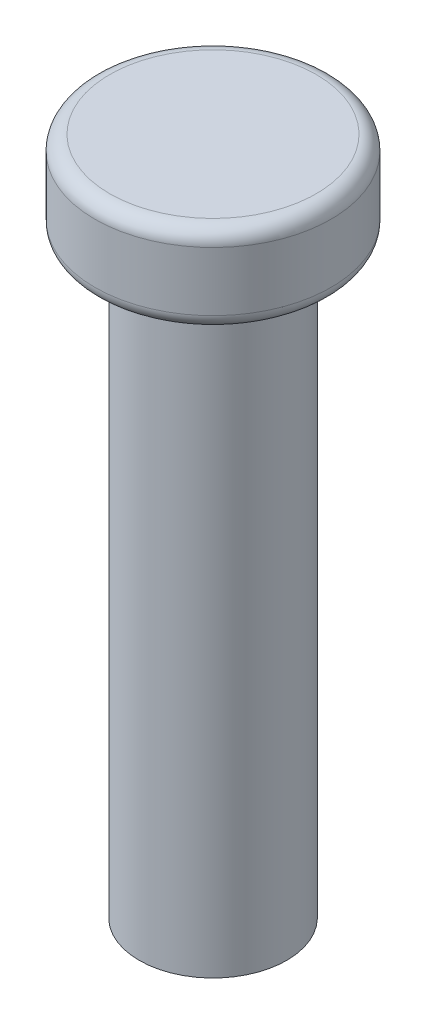
SolidWorks part; units mm, degrees
ref_plane "Front Plane" through (0, 0, 0) normal (0, 0, 1) x (1, 0, 0)
ref_plane "Top Plane" through (0, 0, 0) normal (0, 1, 0) x (1, 0, 0)
ref_plane "Right Plane" through (0, 0, 0) normal (1, 0, 0) x (0, 0, -1)
sketch "Sketch1" plane through (0, 0, 0) normal (0, 1, 0) x (1, 0, 0)
  circle A0 centre (0, 0) radius 2.5
  dimension "D1" = 5
extrude "Boss-Extrude1" add sketch "Sketch1" along normal blind 20
sketch "Sketch2" plane through (0, 20, 0) normal (0, 1, 0) x (1, 0, 0)
  circle A0 centre (0, 0) radius 4
  dimension "D1" = 8
extrude "Boss-Extrude2" add sketch "Sketch2" along normal blind 3
fillet "Fillet1" radius 0.5 1 edges at (0, 23, 4)
fillet "Fillet2" radius 0.5 1 edges at (0, 20, 4)
